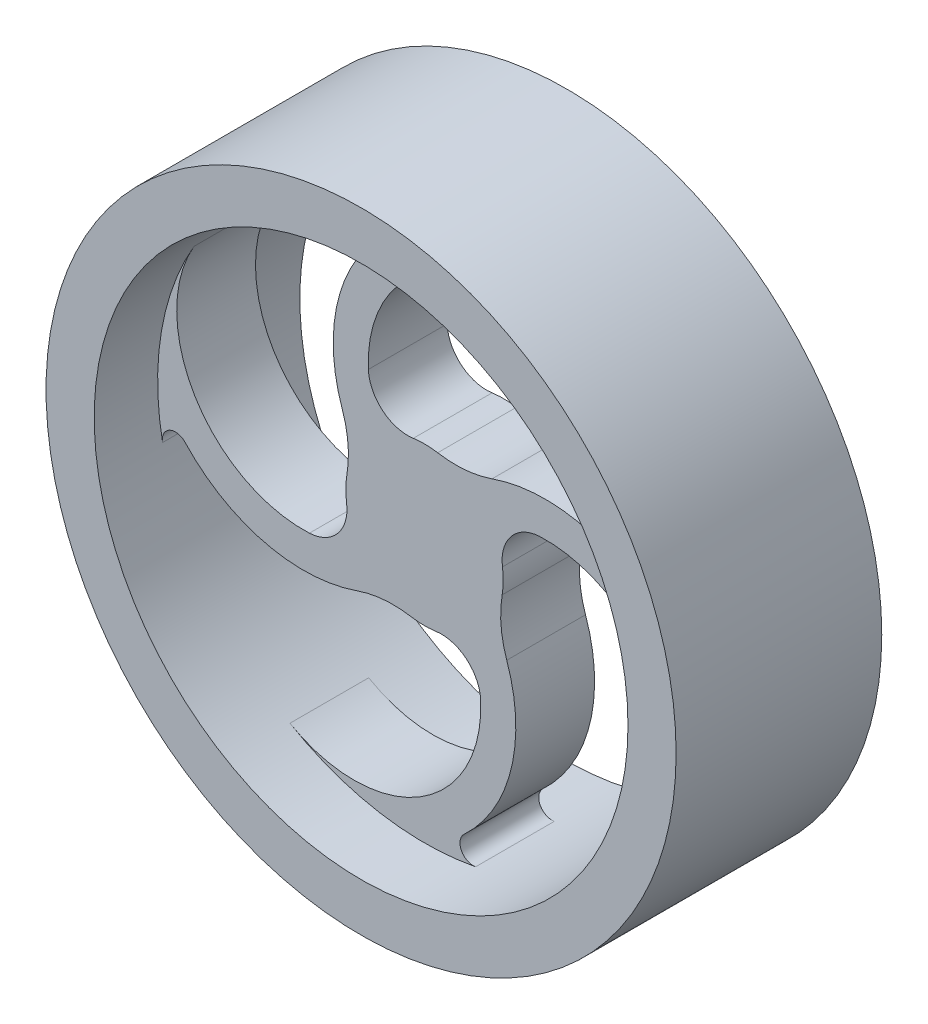
SolidWorks part; units mm, degrees
ref_plane "Front Plane" through (0, 0, 0) normal (0, 0, 1) x (1, 0, 0)
ref_plane "Top Plane" through (0, 0, 0) normal (0, 1, 0) x (1, 0, 0)
ref_plane "Right Plane" through (0, 0, 0) normal (1, 0, 0) x (0, 0, -1)
sketch "Sketch1" plane through (0, 0, 0) normal (0, 0, 1) x (1, 0, 0)
  line L3 (63.5, -55.3297) -> (63.5, -56.1631)
  line L9 (0, 0) -> (-91.3288, 0) construction
  line L10 (0, 0) -> (118.0645, 0) construction
  line L11 (0, 0) -> (0, -87.4912) construction
  line L12 (0, 0) -> (0, 97.6904) construction
  line L14 (9, 0) -> (12, 0)
  line L15 (12, 0) -> (12, 3)
  line L16 (12, 3) -> (8.4853, 3)
  line L17 (8.4853, -3) -> (12, -3)
  line L18 (12, -3) -> (12, 0)
  circle A3 centre (0, 0) radius 72
  arc A4 (-30.7573, -52.6781) -> (11.6777, -59.8718) centre (0, 0) ccw
  arc A5 (-3.0076, -17.7469) -> (2.5629, -17.8166) centre (0, 0) ccw
  arc A6 (52.6781, -30.7573) -> (59.8718, 11.6777) centre (0, 0) ccw
  arc A7 (60.9998, -0.1428) -> (60.931, 0) centre (27.6344, -16.135) ccw
  arc A8 (30.7573, 52.6782) -> (-12.835, 26.3156) centre (16.135, 27.6344) ccw
  arc A9 (-12.835, 26.3156) -> (-2.5629, 17.8166) centre (-3.8443, 26.7249) ccw
  arc A10 (54.7303, 9.0605) -> (15.4307, 18.7945) centre (27.6344, -16.135) ccw
  arc A11 (3.0076, 17.7469) -> (15.4307, 18.7945) centre (7.1849, 42.3955) ccw
  arc A12 (54.7303, 9.0605) -> (59.8718, 11.6777) centre (56.9273, 11.1034) ccw
  arc A13 (-52.6781, 30.7573) -> (-26.3156, -12.835) centre (-27.6344, 16.135) ccw
  arc A14 (-26.3156, -12.835) -> (-17.8166, -2.5629) centre (-26.7249, -3.8443) ccw
  arc A15 (-9.0605, 54.7303) -> (-18.7945, 15.4307) centre (16.135, 27.6344) ccw
  arc A16 (-17.7469, 3.0076) -> (-18.7945, 15.4307) centre (-42.3955, 7.1849) ccw
  arc A17 (-9.0605, 54.7303) -> (-11.6777, 59.8718) centre (-11.1034, 56.9273) ccw
  arc A18 (-30.7573, -52.6781) -> (12.835, -26.3156) centre (-16.135, -27.6344) ccw
  arc A19 (12.835, -26.3156) -> (2.5629, -17.8166) centre (3.8443, -26.7249) ccw
  arc A20 (-54.7303, -9.0605) -> (-15.4307, -18.7945) centre (-27.6344, 16.135) ccw
  arc A21 (-3.0076, -17.7469) -> (-15.4307, -18.7945) centre (-7.1849, -42.3955) ccw
  arc A22 (-54.7303, -9.0605) -> (-59.8718, -11.6777) centre (-56.9273, -11.1034) ccw
  arc A23 (52.6781, -30.7573) -> (26.3156, 12.835) centre (27.6344, -16.135) ccw
  arc A24 (26.3156, 12.835) -> (17.8166, 2.5629) centre (26.7249, 3.8443) ccw
  arc A25 (9.0605, -54.7303) -> (18.7945, -15.4307) centre (-16.135, -27.6344) ccw
  arc A26 (17.7469, -3.0076) -> (18.7945, -15.4307) centre (42.3955, -7.1849) ccw
  arc A27 (9.0605, -54.7303) -> (11.6777, -59.8718) centre (11.1034, -56.9273) ccw
  arc A28 (8.4853, 3) -> (8.4853, -3) centre (0, 0) ccw
  arc A29 (30.7573, 52.6782) -> (-11.6777, 59.8718) centre (0, 0) ccw
  arc A30 (-52.6781, 30.7573) -> (-59.8718, -11.6777) centre (0, 0) ccw
  arc A31 (-17.7469, 3.0076) -> (-17.8166, -2.5629) centre (0, 0) ccw
  arc A32 (3.0076, 17.7469) -> (-2.5629, 17.8166) centre (0, 0) ccw
  arc A33 (17.7469, -3.0076) -> (17.8166, 2.5629) centre (0, 0) ccw
  point P0 (101.222, -40.3713)
  dimension "D1" = 36
  dimension "D2" = 122
  dimension "D3" = 144
  dimension "D4" = 37
  dimension "D5" = 29
  dimension "D6" = 9
  dimension "D7" = 2.5629
  dimension "D8" = 25
  dimension "D9" = 3
  dimension "D10" = 29
  dimension "D11" = 9
  dimension "D12" = 37
  dimension "D13" = 25
  dimension "D14" = 3
  dimension "D15" = 29
  dimension "D16" = 9
  dimension "D17" = 37
  dimension "D18" = 25
  dimension "D19" = 3
  dimension "D20" = 29
  dimension "D21" = 9
  dimension "D22" = 37
  dimension "D23" = 25
  dimension "D24" = 3
  dimension "D25" = 9
  dimension "D26" = 3.0076
  dimension "D27" = 3.8443
  dimension "D28" = 7.1849
  dimension "D29" = 8.4853
  dimension "D30" = 9.0605
  dimension "D31" = 11.1034
  dimension "D32" = 12
  dimension "D33" = 15.4307
  dimension "D34" = 16.135
  dimension "D35" = 17.7469
  dimension "D36" = 17.8166
  dimension "D37" = 30.7573
  dimension "D38" = 54.7303
  dimension "D39" = 63.5
  dimension "D40" = 2.5629
  dimension "D41" = 3.0076
  dimension "D42" = 7.1849
  dimension "D43" = 9.0605
  dimension "D44" = 15.4307
  dimension "D45" = 17.7469
  dimension "D46" = 17.8166
  dimension "D47" = 54.7303
  dimension "D48" = 55.3297
  dimension "D49" = 56.1631
extrude "Boss-Extrude5" add sketch "Sketch1" against normal blind 18 contours A9 A32 A11 A10 A12 A6 A23 A24 A33 A26 A25 A27 A4 A18 A19 A5 A21 A20 A22 A30 A13 A14 A31 A16 A15 A17 A29 A8
sketch "Sketch5" plane through (0, 0, 0) normal (0, 0, 1) x (1, 0, 0)
  circle A0 centre (0, 0) radius 72
  circle A1 centre (0, 0) radius 61
  dimension "D1" = 144
extrude "Boss-Extrude6" add sketch "Sketch5" against normal blind 32.5 and the other way blind 14.5
sketch "Sketch6" plane through (0, 0, 0) normal (0, 0, 1) x (1, 0, 0)
  circle A0 centre (0, 0) radius 18
  circle A1 centre (0, 0) radius 10
  dimension "D1" = 36
  dimension "D2" = 20
